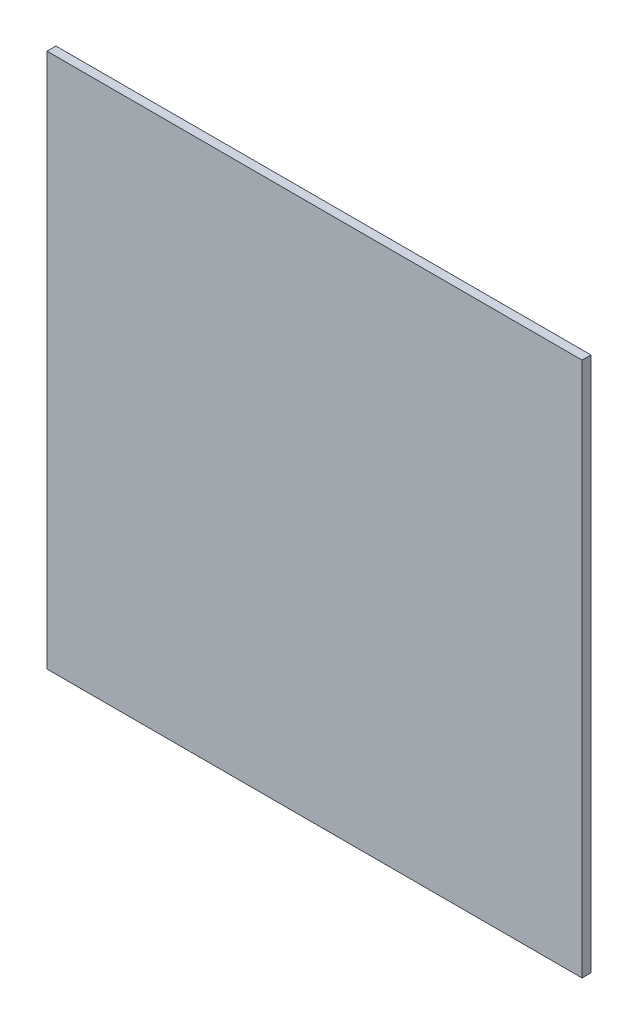
SolidWorks part; units mm, degrees
ref_plane "Front Plane" through (0, 0, 0) normal (0, 0, 1) x (1, 0, 0)
ref_plane "Top Plane" through (0, 0, 0) normal (0, 1, 0) x (1, 0, 0)
ref_plane "Right Plane" through (0, 0, 0) normal (1, 0, 0) x (0, 0, -1)
sketch "Sketch1" plane through (0, 0, 0) normal (0, 0, 1) x (1, 0, 0)
  line L1 (150, -150) -> (-150, -150)
  line L2 (150, -150) -> (150, 150)
  line L3 (150, 150) -> (-150, 150)
  line L4 (-150, -150) -> (-150, 150)
  line L5 (150, -150) -> (-150, 150) construction
  line L6 (150, 150) -> (-150, -150) construction
  point P0 (0, 0)
  dimension "D1" = 300
  dimension "D2" = 300
extrude "Boss-Extrude1" add sketch "Sketch1" along normal blind 5
